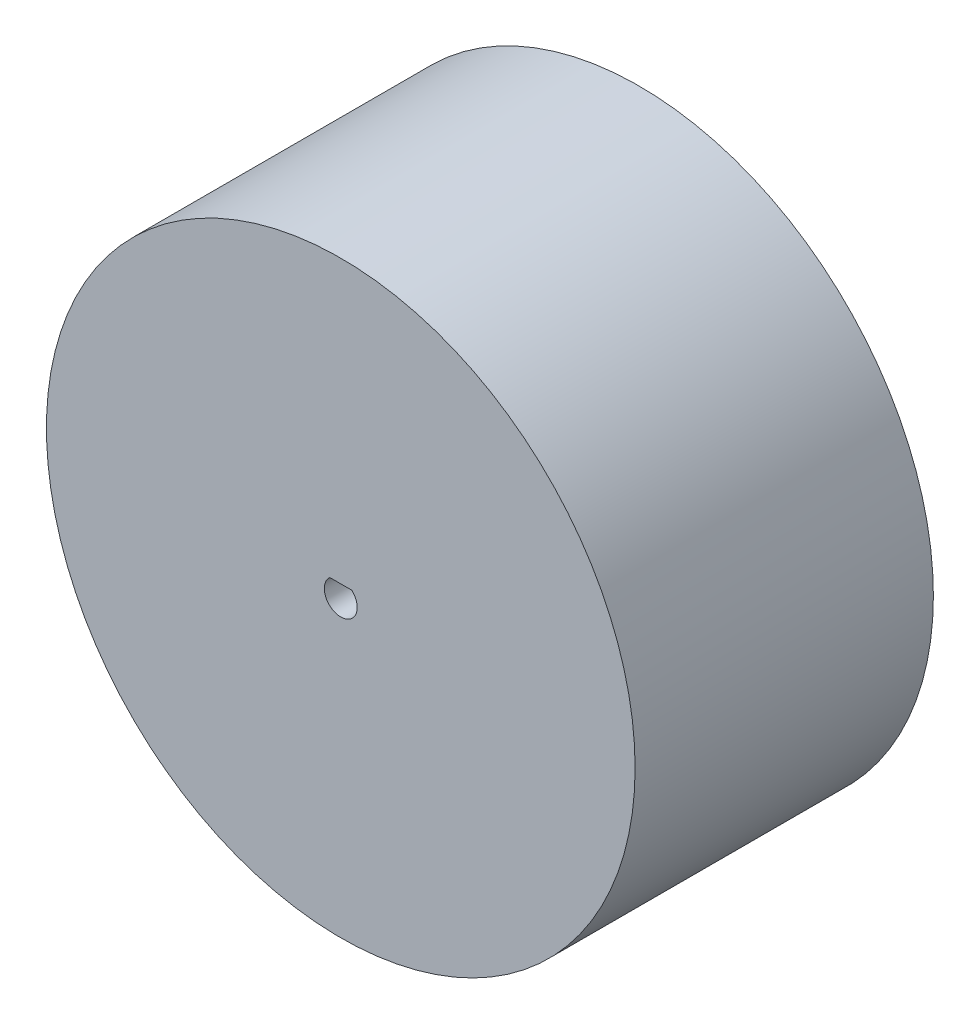
SolidWorks part; units mm, degrees
ref_plane "Front Plane" through (0, 0, 0) normal (0, 0, 1) x (1, 0, 0)
ref_plane "Top Plane" through (0, 0, 0) normal (0, 1, 0) x (1, 0, 0)
ref_plane "Right Plane" through (0, 0, 0) normal (1, 0, 0) x (0, 0, -1)
sketch "Sketch1" plane through (0, 0, 0) normal (0, 0, 1) x (1, 0, 0)
  circle A0 centre (0, 0) radius 37.5
  dimension "D1" = 75
extrude "Boss-Extrude1" add sketch "Sketch1" along normal blind 38
sketch "Sketch2" plane through (0, 0, 38) normal (0, 0, 1) x (1, 0, 0)
  line L0 (-1.397, 1.5619) -> (1.397, 1.5619)
  arc A2 (-1.397, 1.5619) -> (1.397, 1.5619) centre (0, 0) ccw
  dimension "D1" = 2.0955
  dimension "D2" = 2.794
extrude "Cut-Extrude1" cut sketch "Sketch2" against normal through all both and the other way through all contours L0 A2
